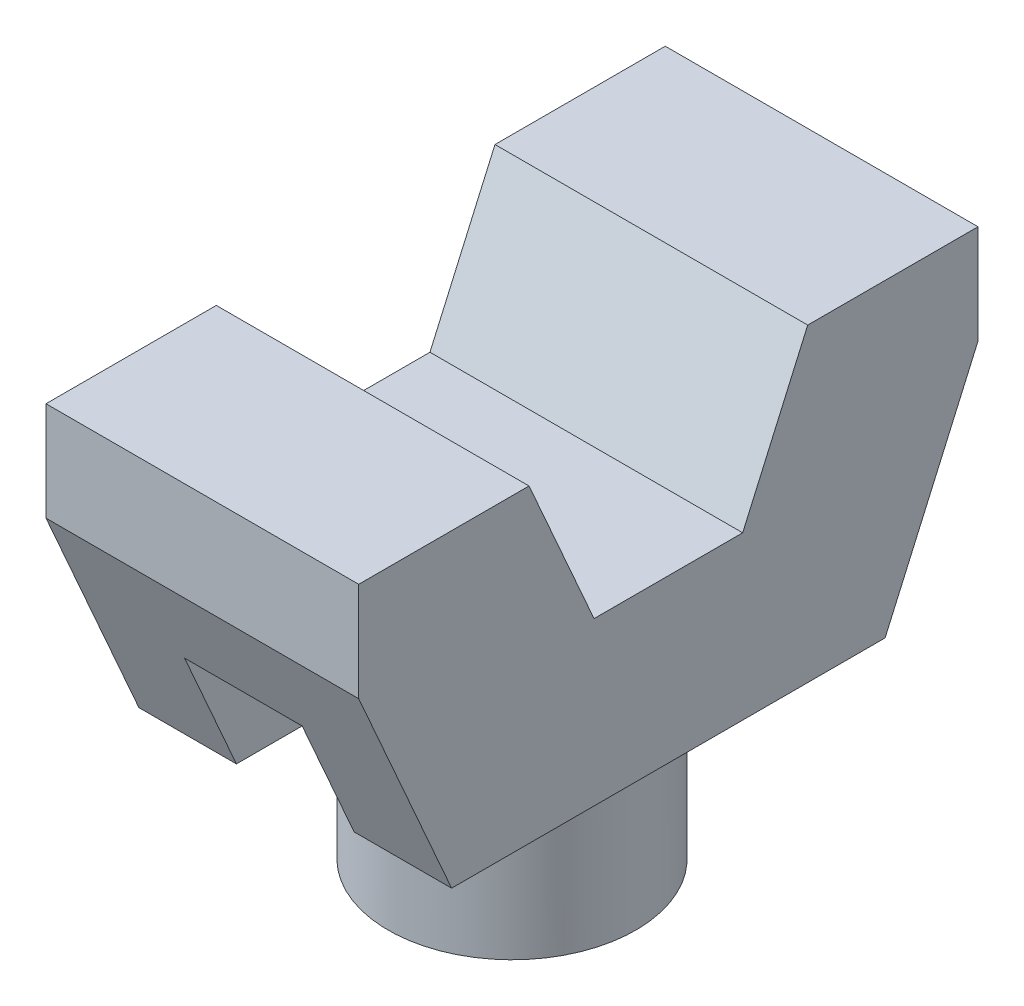
SolidWorks part; units mm, degrees
ref_plane "Front Plane" through (0, 0, 0) normal (0, 0, 1) x (1, 0, 0)
ref_plane "Top Plane" through (0, 0, 0) normal (0, 1, 0) x (1, 0, 0)
ref_plane "Right Plane" through (0, 0, 0) normal (1, 0, 0) x (0, 0, -1)
sketch "Sketch1" plane through (0, 0, 0) normal (1, 0, 0) x (0, 0, -1)
  line L10 (-12, 0) -> (12, 0)
  line L11 (12, 0) -> (22.5, 23.8)
  line L12 (22.5, 23.8) -> (50, 23.8)
  line L13 (50, 23.8) -> (50, 7.8)
  line L14 (50, 7.8) -> (35, -26.2)
  line L15 (35, -26.2) -> (-35, -26.2)
  line L16 (-35, -26.2) -> (-50, 7.8)
  line L17 (-50, 7.8) -> (-50, 23.8)
  line L18 (-50, 23.8) -> (-22.5, 23.8)
  line L19 (-22.5, 23.8) -> (-12, 0)
  dimension "D1" = 12
  dimension "D2" = 12
  dimension "D3" = 22.5
  dimension "D4" = 22.5
  dimension "D5" = 27.5
  dimension "D6" = 100
  dimension "D7" = 16
  dimension "D8" = 16
  dimension "D9" = 50
  dimension "D10" = 50
  dimension "D11" = 35
  dimension "D12" = 35
extrude "Boss-Extrude1" add sketch "Sketch1" against normal blind 50.5
sketch "Sketch2" plane through (0, -26.2, 0) normal (0, -1, 0) x (1, 0, 0)
  line L0 (0, 35) -> (0, -35) construction
  line L2 (-50.5, 35) -> (-50.5, -35) construction
  circle A0 centre (-25.25, 0) radius 20
  point P2 (0, 0)
  dimension "D1" = 40
  dimension "D3" = 25.25
  dimension "D2" = 25.25
extrude "Boss-Extrude2" add sketch "Sketch2" along normal blind 26 contours A0
sketch "Sketch4" plane through (0, 0, 50) normal (0, 0, 1) x (1, 0, 0)
  line L0 (0, 7.8) -> (0, -26.2) construction
  line L1 (-34.75, -7.2) -> (-15.75, -7.2)
  line L2 (-34.75, -7.2) -> (-34.75, -26.2)
  line L3 (-34.75, -26.2) -> (-15.75, -26.2)
  line L4 (-15.75, -7.2) -> (-15.75, -26.2)
  line L5 (-50.5, 7.8) -> (-50.5, -26.2) construction
  line L6 (-45.25, -26.2) -> (-5.25, -26.2) construction
  point P5 (0, 0)
  dimension "D1" = 15.75
  dimension "D2" = 15.75
  dimension "D3" = 0
  dimension "D4" = 19
extrude "Cut-Extrude1" cut sketch "Sketch4" against normal blind 30 contours L3 L4 L1 L2
sketch "Sketch5" plane through (0, 0, -50) normal (0, 0, -1) x (-1, 0, 0)
  line L0 (50.5, -26.2) -> (50.5, 7.8) construction
  line L1 (15.75, -7.2) -> (34.75, -7.2)
  line L2 (15.75, -7.2) -> (15.75, -26.2)
  line L3 (15.75, -26.2) -> (34.75, -26.2)
  line L4 (34.75, -7.2) -> (34.75, -26.2)
  line L5 (0, -26.2) -> (0, 7.8) construction
  line L6 (5.25, -26.2) -> (45.25, -26.2) construction
  point P5 (0, 0)
  dimension "D1" = 15.75
  dimension "D2" = 15.75
  dimension "D3" = 0
  dimension "D4" = 19
extrude "Cut-Extrude2" cut sketch "Sketch5" against normal blind 30 contours L3 L4 L1 L2
